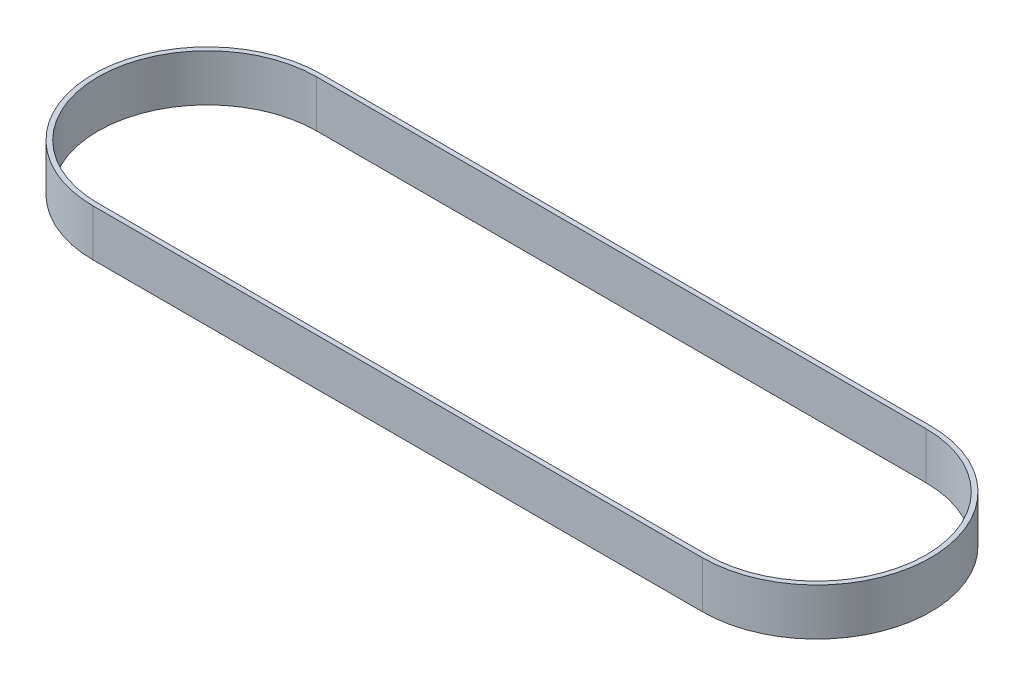
SolidWorks part; units mm, degrees
ref_plane "Front Plane" through (0, 0, 0) normal (0, 0, 1) x (1, 0, 0)
ref_plane "Top Plane" through (0, 0, 0) normal (0, 1, 0) x (1, 0, 0)
ref_plane "Right Plane" through (0, 0, 0) normal (1, 0, 0) x (0, 0, -1)
sketch "Sketch1" plane through (0, 0, 0) normal (0, 1, 0) x (1, 0, 0)
  line L0 (0, 0) -> (195.0466, 0) construction
  line L1 (0, 35.0139) -> (195.0466, 35.0139)
  line L2 (0, -35.0139) -> (195.0466, -35.0139)
  line L3 (0, -36.5379) -> (195.0466, -36.5379)
  line L4 (0, 36.5379) -> (195.0466, 36.5379)
  arc A0 (0, 35.0139) -> (0, -35.0139) centre (0, 0) ccw
  arc A1 (195.0466, -35.0139) -> (195.0466, 35.0139) centre (195.0466, 0) ccw
  arc A2 (0, 36.5379) -> (0, -36.5379) centre (0, 0) ccw
  arc A3 (195.0466, -36.5379) -> (195.0466, 36.5379) centre (195.0466, 0) ccw
  dimension "D2" = 70.0278
  dimension "D3" = 195.0466
  dimension "D4" = 1.524
extrude "Boss-Extrude1" add sketch "Sketch1" along normal blind 15
